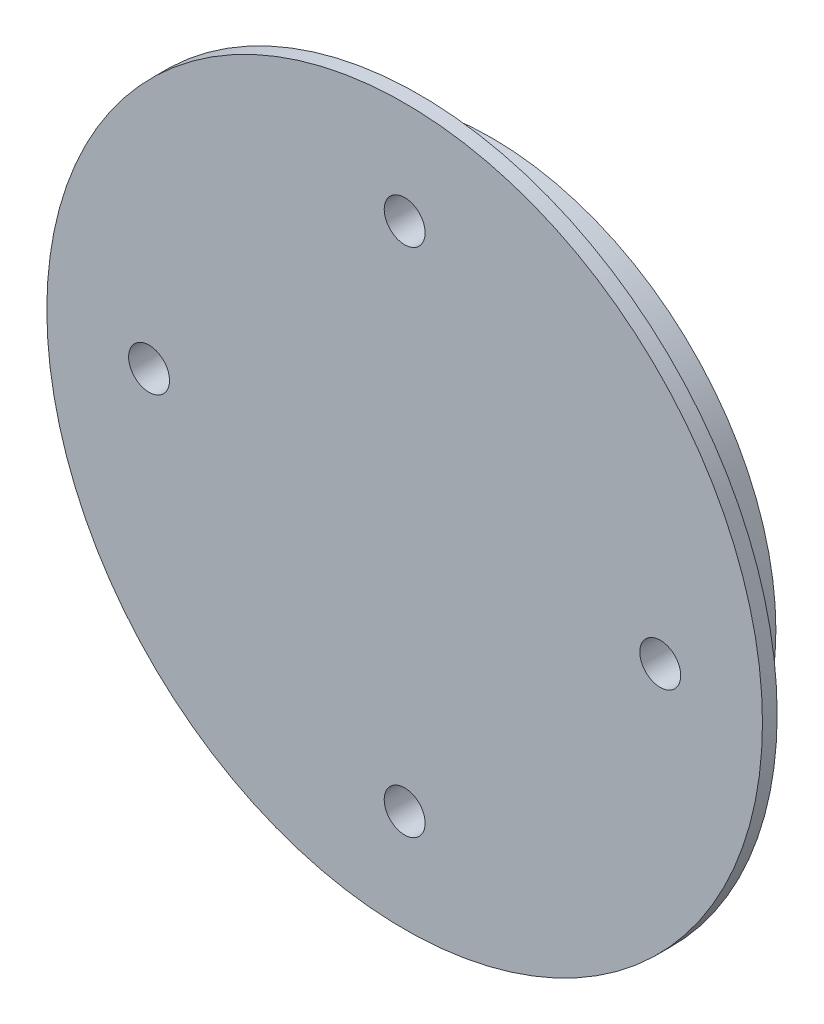
SolidWorks part; units mm, degrees
material "ABS"
ref_plane "正面" through (0, 0, 0) normal (0, 0, 1) x (1, 0, 0)
ref_plane "平面" through (0, 0, 0) normal (0, 1, 0) x (1, 0, 0)
ref_plane "右側面" through (0, 0, 0) normal (1, 0, 0) x (0, 0, -1)
sketch "ｽｹｯﾁ1" plane through (0, 0, 0) normal (0, 0, 1) x (1, 0, 0)
  circle A0 centre (0, 0) radius 23.5
  dimension "D1" = 47
extrude "ﾎﾞｽ - 押し出し1" add sketch "ｽｹｯﾁ1" along normal blind 2.5
sketch "ｽｹｯﾁ2" plane through (0, 0, 0) normal (0, 0, -1) x (-1, 0, 0)
  circle A0 centre (0, 0) radius 22.225
  dimension "D1" = 44.45
extrude "ﾎﾞｽ - 押し出し2" add sketch "ｽｹｯﾁ2" along normal blind 3.175
sketch "ｽｹｯﾁ3" plane through (0, 0, -3.175) normal (0, 0, -1) x (-1, 0, 0)
  circle A0 centre (0, 0) radius 20 construction
  circle A1 centre (0, 20) radius 1.6
  circle A2 centre (20, 0) radius 1.6
  circle A3 centre (0, -20) radius 1.6
  circle A4 centre (-20, 0) radius 1.6
  point P14 (0, 0)
  dimension "D1" = 40
  dimension "D2" = 3.2
  dimension "D3" = 4
extrude "ｶｯﾄ - 押し出し1" cut sketch "ｽｹｯﾁ3" against normal through all
sketch "ｽｹｯﾁ4" plane through (0, 0, 2.5) normal (0, 0, 1) x (1, 0, 0)
  circle A0 centre (0, 0) radius 28
  circle A1 centre (0, 20) radius 1.6 construction
  circle A2 centre (-20, 0) radius 1.6 construction
  circle A3 centre (0, -20) radius 1.6 construction
  circle A4 centre (20, 0) radius 1.6 construction
  circle A5 centre (0, 20) radius 1.6
  circle A6 centre (-20, 0) radius 1.6
  circle A7 centre (0, -20) radius 1.6
  circle A8 centre (20, 0) radius 1.6
  dimension "D1" = 56
extrude "ﾎﾞｽ - 押し出し3" add sketch "ｽｹｯﾁ4" along normal blind 1.15
